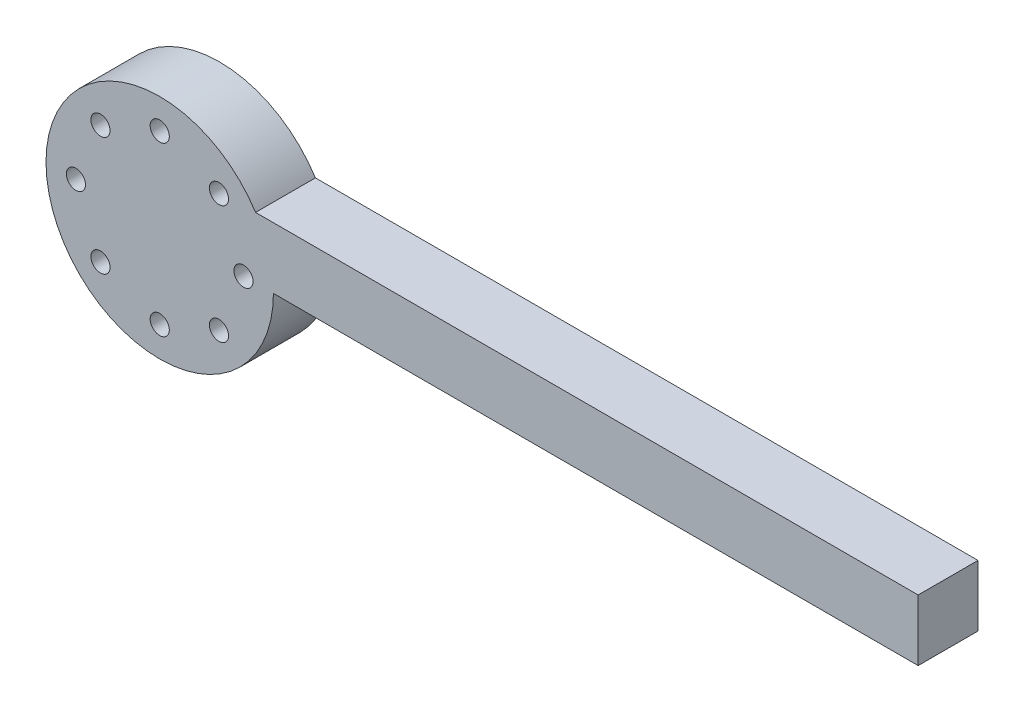
SolidWorks part; units mm, degrees
ref_plane "Front Plane" through (0, 0, 0) normal (0, 0, 1) x (1, 0, 0)
ref_plane "Top Plane" through (0, 0, 0) normal (0, 1, 0) x (1, 0, 0)
ref_plane "Right Plane" through (0, 0, 0) normal (1, 0, 0) x (0, 0, -1)
sketch "Sketch1" plane through (0, 0, 0) normal (0, 0, 1) x (1, 0, 0)
  circle A0 centre (0, 0) radius 9.5
  dimension "D1" = 19
extrude "Boss-Extrude1" add sketch "Sketch1" along normal blind 5
sketch "Sketch3" plane through (0, 0, 0) normal (0, 0, -1) x (-1, 0, 0)
  line L0 (-8.0072, 5.1123) -> (-63.3627, 5.1123)
  line L1 (-63.3627, 5.1123) -> (-63.3627, 0)
  line L2 (-63.3627, 0) -> (-9.5, 0)
  circle A0 centre (0, 0) radius 9.5 construction
  arc A1 (-8.0072, 5.1123) -> (-9.5, 0) centre (0, 0) ccw
extrude "Boss-Extrude2" add sketch "Sketch3" against normal up to surface (5 mm away) up to face at (9.5, 0, 5)
sketch "Sketch4" plane through (0, 0, 0) normal (0, 0, -1) x (-1, 0, 0)
  circle A0 centre (0, 7) radius 0.8
  circle A1 centre (4.9497, 4.9497) radius 0.8
  circle A2 centre (7, 0) radius 0.8
  circle A3 centre (4.9497, -4.9497) radius 0.8
  circle A4 centre (0, -7) radius 0.8
  circle A5 centre (-4.9497, -4.9497) radius 0.8
  circle A6 centre (-7, 0) radius 0.8
  circle A7 centre (-4.9497, 4.9497) radius 0.8
  point P20 (0, 0)
  dimension "D2" = 1.6
  dimension "D1" = 7
  dimension "D3" = 8
extrude "Cut-Extrude1" cut sketch "Sketch4" against normal through all
